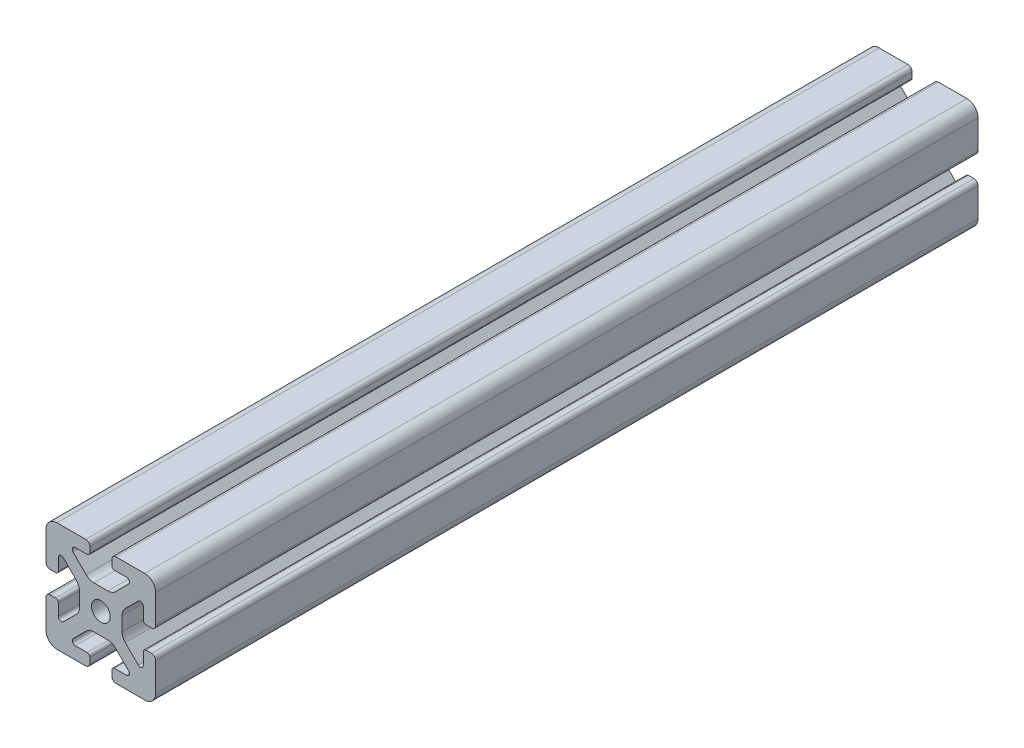
SolidWorks part; units mm, degrees
ref_plane "Front Plane" through (0, 0, 0) normal (0, 0, 1) x (1, 0, 0)
ref_plane "Top Plane" through (0, 0, 0) normal (0, 1, 0) x (1, 0, 0)
ref_plane "Right Plane" through (0, 0, 0) normal (1, 0, 0) x (0, 0, -1)
sketch "Sketch1" plane through (0, 0, 0) normal (0, 0, 1) x (1, 0, 0)
  line L0 (-9.343, 15.5) -> (-5, 15.5)
  line L1 (-16, -20) -> (-5.5, -20)
  line L2 (-20, -16) -> (-20, -5.5)
  line L3 (-16, 20) -> (-5.5, 20)
  line L4 (20, -16) -> (20, -5.5)
  line L5 (-20, -20) -> (20, 20) construction
  line L6 (-20, 20) -> (20, -20) construction
  line L7 (15.5, 9.343) -> (15.5, 5)
  line L8 (-9.343, -15.5) -> (-5, -15.5)
  line L9 (-4, 18.5) -> (-4, 16.5)
  line L10 (-15.5, 9.343) -> (-15.5, 5)
  line L11 (4, 18.5) -> (4, 16.5)
  line L12 (-10.1066, 13.6563) -> (-5.3719, 8.9216)
  line L13 (-13.6563, 10.1066) -> (-8.9216, 5.3719)
  line L14 (-18.5, 4) -> (-16.5, 4)
  line L15 (16.5, 4) -> (18.5, 4)
  line L16 (16.5, -4) -> (18.5, -4)
  line L17 (-16.5, -4) -> (-18.5, -4)
  line L18 (-4, -16.5) -> (-4, -18.5)
  line L19 (4, -16.5) -> (4, -18.5)
  line L20 (-13.6563, -10.1066) -> (-8.9216, -5.3719)
  line L21 (-10.1066, -13.6563) -> (-5.3719, -8.9216)
  line L22 (-2.5435, 7.75) -> (2.5435, 7.75)
  line L23 (-2.5435, -7.75) -> (2.5435, -7.75)
  line L24 (7.75, 2.5435) -> (7.75, -2.5435)
  line L25 (-7.75, 2.5435) -> (-7.75, -2.5435)
  line L30 (5.3719, -8.9216) -> (10.1066, -13.6563)
  line L31 (8.9216, 5.3719) -> (13.6563, 10.1066)
  line L32 (8.9216, -5.3719) -> (13.6563, -10.1066)
  line L33 (5.3719, 8.9216) -> (10.1066, 13.6563)
  line L34 (5.5, 20) -> (16, 20)
  line L35 (5, 15.5) -> (9.343, 15.5)
  line L36 (20, 5.5) -> (20, 16)
  line L37 (15.5, -5) -> (15.5, -9.343)
  line L38 (-15.5, -5) -> (-15.5, -9.343)
  line L39 (-20, 5.5) -> (-20, 16)
  line L40 (5.5, -20) -> (16, -20)
  line L41 (5, -15.5) -> (9.343, -15.5)
  circle A0 centre (0, 0) radius 3.4
  arc A1 (7.75, -2.5435) -> (8.9216, -5.3719) centre (11.75, -2.5435) ccw
  arc A2 (7.75, 2.5435) -> (8.9216, 5.3719) centre (11.75, 2.5435) cw
  arc A3 (2.5435, 7.75) -> (5.3719, 8.9216) centre (2.5435, 11.75) ccw
  arc A4 (-2.5435, 7.75) -> (-5.3719, 8.9216) centre (-2.5435, 11.75) cw
  arc A5 (-7.75, 2.5435) -> (-8.9216, 5.3719) centre (-11.75, 2.5435) ccw
  arc A6 (-7.75, -2.5435) -> (-8.9216, -5.3719) centre (-11.75, -2.5435) cw
  arc A7 (-2.5435, -7.75) -> (-5.3719, -8.9216) centre (-2.5435, -11.75) ccw
  arc A8 (-16, -20) -> (-20, -16) centre (-16, -16) cw
  arc A9 (16, -20) -> (20, -16) centre (16, -16) ccw
  arc A10 (16, 20) -> (20, 16) centre (16, 16) cw
  arc A11 (-20, 16) -> (-16, 20) centre (-16, 16) cw
  arc A12 (-18.5, -4) -> (-20, -5.5) centre (-18.5, -5.5) ccw
  arc A13 (-4, -18.5) -> (-5.5, -20) centre (-5.5, -18.5) cw
  arc A14 (4, -18.5) -> (5.5, -20) centre (5.5, -18.5) ccw
  arc A15 (18.5, -4) -> (20, -5.5) centre (18.5, -5.5) cw
  arc A16 (18.5, 4) -> (20, 5.5) centre (18.5, 5.5) ccw
  arc A17 (4, 18.5) -> (5.5, 20) centre (5.5, 18.5) cw
  arc A18 (-4, 18.5) -> (-5.5, 20) centre (-5.5, 18.5) ccw
  arc A19 (-18.5, 4) -> (-20, 5.5) centre (-18.5, 5.5) cw
  arc A20 (-16.5, -4) -> (-15.5, -5) centre (-16.5, -5) cw
  arc A21 (-4, -16.5) -> (-5, -15.5) centre (-5, -16.5) ccw
  arc A22 (4, -16.5) -> (5, -15.5) centre (5, -16.5) cw
  arc A23 (16.5, -4) -> (15.5, -5) centre (16.5, -5) ccw
  arc A24 (16.5, 4) -> (15.5, 5) centre (16.5, 5) cw
  arc A25 (4, 16.5) -> (5, 15.5) centre (5, 16.5) ccw
  arc A26 (-4, 16.5) -> (-5, 15.5) centre (-5, 16.5) cw
  arc A27 (-16.5, 4) -> (-15.5, 5) centre (-16.5, 5) ccw
  arc A28 (-13.6563, -10.1066) -> (-15.5, -9.343) centre (-14.42, -9.343) cw
  arc A29 (-10.1066, -13.6563) -> (-9.343, -15.5) centre (-9.343, -14.42) ccw
  arc A30 (10.1066, -13.6563) -> (9.343, -15.5) centre (9.343, -14.42) cw
  arc A31 (13.6563, -10.1066) -> (15.5, -9.343) centre (14.42, -9.343) ccw
  arc A32 (13.6563, 10.1066) -> (15.5, 9.343) centre (14.42, 9.343) cw
  arc A33 (10.1066, 13.6563) -> (9.343, 15.5) centre (9.343, 14.42) ccw
  arc A34 (-10.1066, 13.6563) -> (-9.343, 15.5) centre (-9.343, 14.42) cw
  arc A35 (-13.6563, 10.1066) -> (-15.5, 9.343) centre (-14.42, 9.343) ccw
  arc A36 (2.5435, -7.75) -> (5.3719, -8.9216) centre (2.5435, -11.75) cw
  point P0 (0, 0)
  point P8 (7.75, -4.2003)
  point P12 (7.75, 4.2003)
  point P50 (4.2003, 7.75)
  point P77 (4, -20)
  point P82 (20, 4)
  point P85 (4, 20)
  point P90 (-20, 4)
  point P93 (-15.5, -4)
  point P98 (4, -15.5)
  point P101 (15.5, -4)
  point P106 (4, 15.5)
  point P109 (-4, 15.5)
  point P114 (-15.5, -11.9503)
  point P119 (11.9503, -15.5)
  point P122 (15.5, -11.9503)
  point P127 (11.9503, 15.5)
  point P134 (4.2003, -7.75)
  dimension "D10" = 6.8
  dimension "D15" = 4
  dimension "D16" = 1.5
  dimension "D17" = 1
  dimension "D18" = 1.08
  dimension "D19" = 4
  dimension "D1" = 40
  dimension "D2" = 4.5
  dimension "D3" = 4.5
  dimension "D4" = 4.5
  dimension "D5" = 4.5
  dimension "D6" = 16
  dimension "D7" = 16
  dimension "D8" = 16
  dimension "D9" = 16
  dimension "D11" = 5.02
  dimension "D12" = 5.02
  dimension "D13" = 15.5
  dimension "D14" = 15.5
  dimension "D20" = 40
extrude "Boss-Extrude1" add sketch "Sketch1" along normal blind 300
